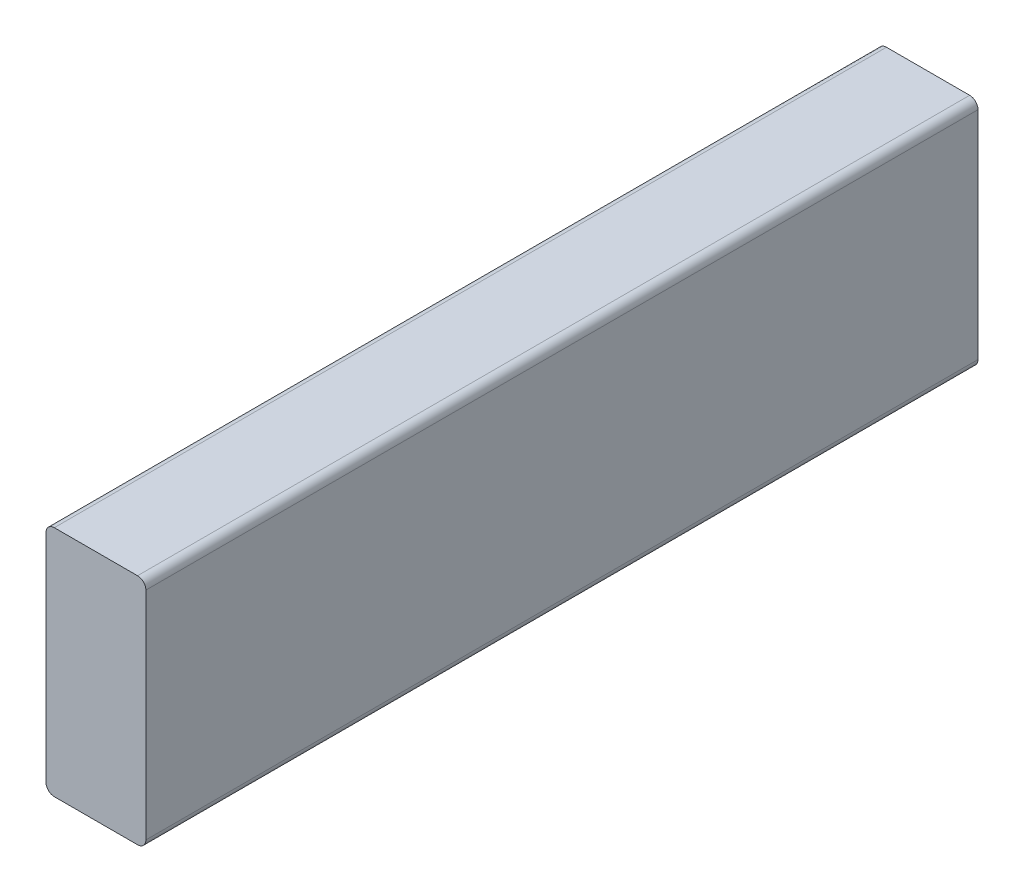
SolidWorks part; units mm, degrees
material "Pine"
ref_plane "Front Plane" through (0, 0, 0) normal (0, 0, 1) x (1, 0, 0)
ref_plane "Top Plane" through (0, 0, 0) normal (0, 1, 0) x (1, 0, 0)
ref_plane "Right Plane" through (0, 0, 0) normal (1, 0, 0) x (0, 0, -1)
sketch "Sketch1" plane through (0, 0, 0) normal (1, 0, 0) x (0, 0, -1)
  line L1 (-158.75, 88.9) -> (158.75, 88.9)
  line L2 (-158.75, 88.9) -> (-158.75, 0)
  line L3 (-158.75, 0) -> (158.75, 0)
  line L4 (158.75, 88.9) -> (158.75, 0)
  point P4 (0, 0)
  dimension "D1" = 317.5
  dimension "D2" = 88.9
extrude "Boss-Extrude1" add sketch "Sketch1" along normal mid plane 38.1
fillet "Fillet1" radius 3.175 4 edges at (-19.05, 0, 0) (19.05, 0, 0) (-19.05, 88.9, 0) (19.05, 88.9, 0)
